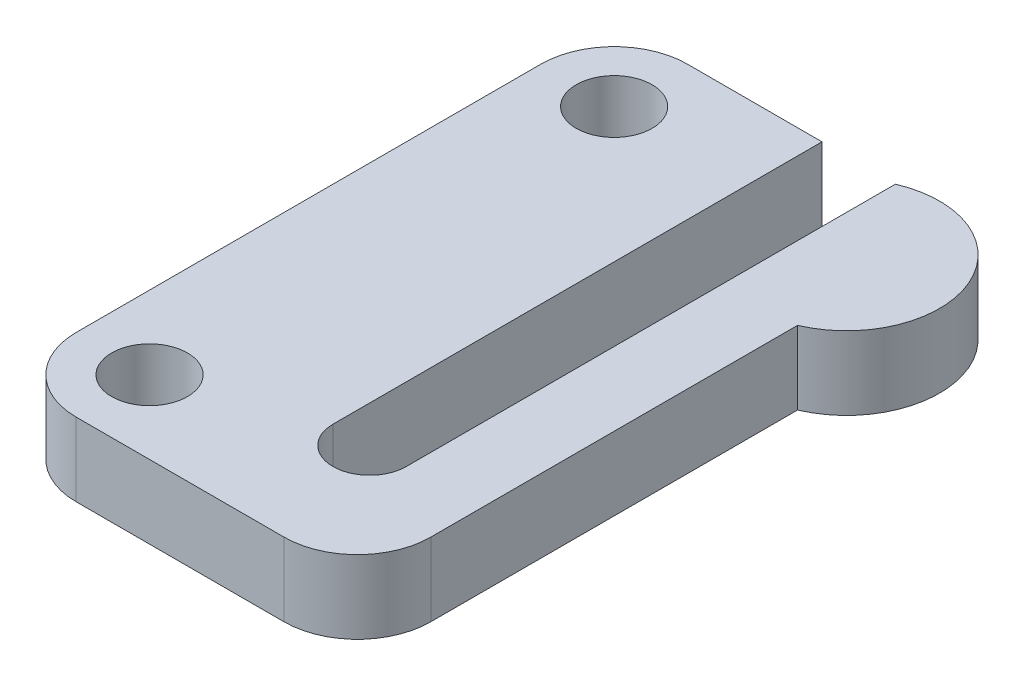
SolidWorks part; units mm, degrees
ref_plane "Front Plane" through (0, 0, 0) normal (0, 0, 1) x (1, 0, 0)
ref_plane "Top Plane" through (0, 0, 0) normal (0, 1, 0) x (1, 0, 0)
ref_plane "Right Plane" through (0, 0, 0) normal (1, 0, 0) x (0, 0, -1)
sketch "Sketch1" plane through (0, 0, 0) normal (0, 1, 0) x (1, 0, 0)
  line L0 (2, -7.5) -> (2, 5.5)
  line L2 (-12.5, -12.5) -> (-12.5, 12.5)
  line L5 (-12.5, -12.5) -> (2, -12.5)
  line L6 (2, -12.5) -> (2, -7.5)
  line L7 (2, 5.5) -> (2, 12.5) construction
  line L9 (-1, 12.5) -> (-1, -7.5)
  line L11 (-1, -7.5) -> (-4, -7.5) construction
  line L13 (-4, 12.5) -> (-12.5, 12.5)
  line L14 (-4, -7.5) -> (-4, 12.5)
  circle A0 centre (-9.5, 9.5) radius 1.55
  circle A1 centre (-9.5, -9.5) radius 1.55
  arc A3 (-1, -7.5) -> (-4, -7.5) centre (-2.5, -7.5) cw
  arc A4 (2, 5.5) -> (-1, 12.5) centre (0.5, 9) ccw
  point P0 (0, 0)
  dimension "D3" = 3.1
  dimension "D6" = 7
  dimension "D1" = 3
  dimension "D2" = 25
  dimension "D4" = 3
  dimension "D8" = 14.5
  dimension "D5" = 2
extrude "Boss-Extrude1" add sketch "Sketch1" against normal blind 3
fillet "Fillet1" radius 3 1 edges at (2, -1.5, 12.5)
fillet "Fillet3" radius 3 2 edges at (-12.5, -1.5, 12.5) (-12.5, -1.5, -12.5)
